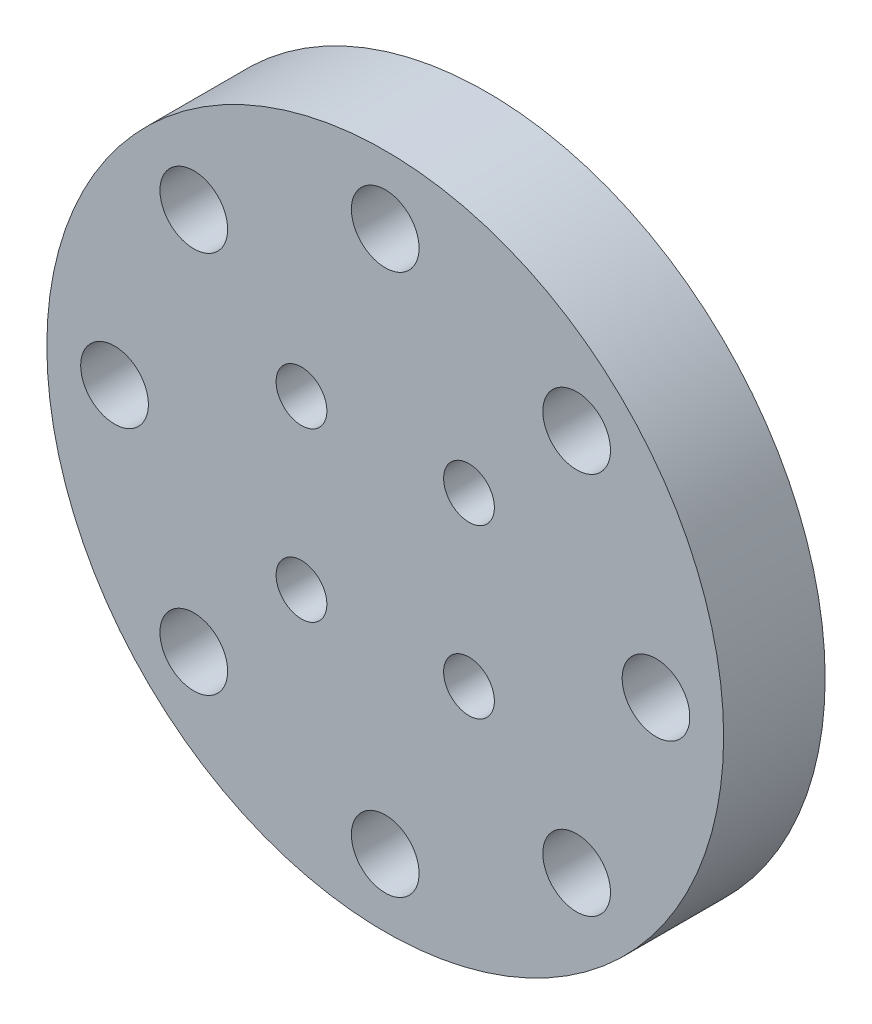
SolidWorks part; units mm, degrees
ref_plane "Front Plane" through (0, 0, 0) normal (0, 0, 1) x (1, 0, 0)
ref_plane "Top Plane" through (0, 0, 0) normal (0, 1, 0) x (1, 0, 0)
ref_plane "Right Plane" through (0, 0, 0) normal (1, 0, 0) x (0, 0, -1)
sketch "Sketch1" plane through (0, 0, 0) normal (0, 0, 1) x (1, 0, 0)
  circle A0 centre (0, 0) radius 20
  dimension "D1" = 40
extrude "Boss-Extrude1" add sketch "Sketch1" along normal blind 6
sketch "Sketch2" plane through (0, 0, 0) normal (0, 0, -1) x (-1, 0, 0)
  line L0 (0, 0) -> (0, 16) construction
  line L1 (0, 0) -> (-4.9497, -4.9497) construction
  circle A0 centre (0, 16) radius 2
  circle A1 centre (11.3137, 11.3137) radius 2
  circle A2 centre (16, 0) radius 2
  circle A3 centre (11.3137, -11.3137) radius 2
  circle A4 centre (0, -16) radius 2
  circle A5 centre (-11.3137, -11.3137) radius 2
  circle A6 centre (-16, 0) radius 2
  circle A7 centre (-11.3137, 11.3137) radius 2
  circle A8 centre (-4.9497, -4.9497) radius 1.5
  circle A9 centre (-4.9497, 4.9497) radius 1.5
  circle A10 centre (4.9497, 4.9497) radius 1.5
  circle A11 centre (4.9497, -4.9497) radius 1.5
  point P20 (0, 0)
  point P30 (0, 0)
  dimension "D2" = 4
  dimension "D6" = 3
  dimension "D1" = 16
  dimension "D4" = 7
  dimension "D5" = 45
  dimension "D3" = 8
  dimension "D7" = 4
extrude "Cut-Extrude1" cut sketch "Sketch2" against normal blind 6
sketch "Sketch4" plane through (0, 0, 0) normal (0, 0, -1) x (-1, 0, 0)
  circle A0 centre (-4.9497, 4.9497) radius 3
  circle A1 centre (4.9497, 4.9497) radius 3
  circle A2 centre (4.9497, -4.9497) radius 3
  circle A3 centre (-4.9497, -4.9497) radius 3
  point P12 (0, 0)
  dimension "D1" = 6
  dimension "D2" = 4
extrude "Cut-Extrude2" cut sketch "Sketch4" against normal blind 3.1
